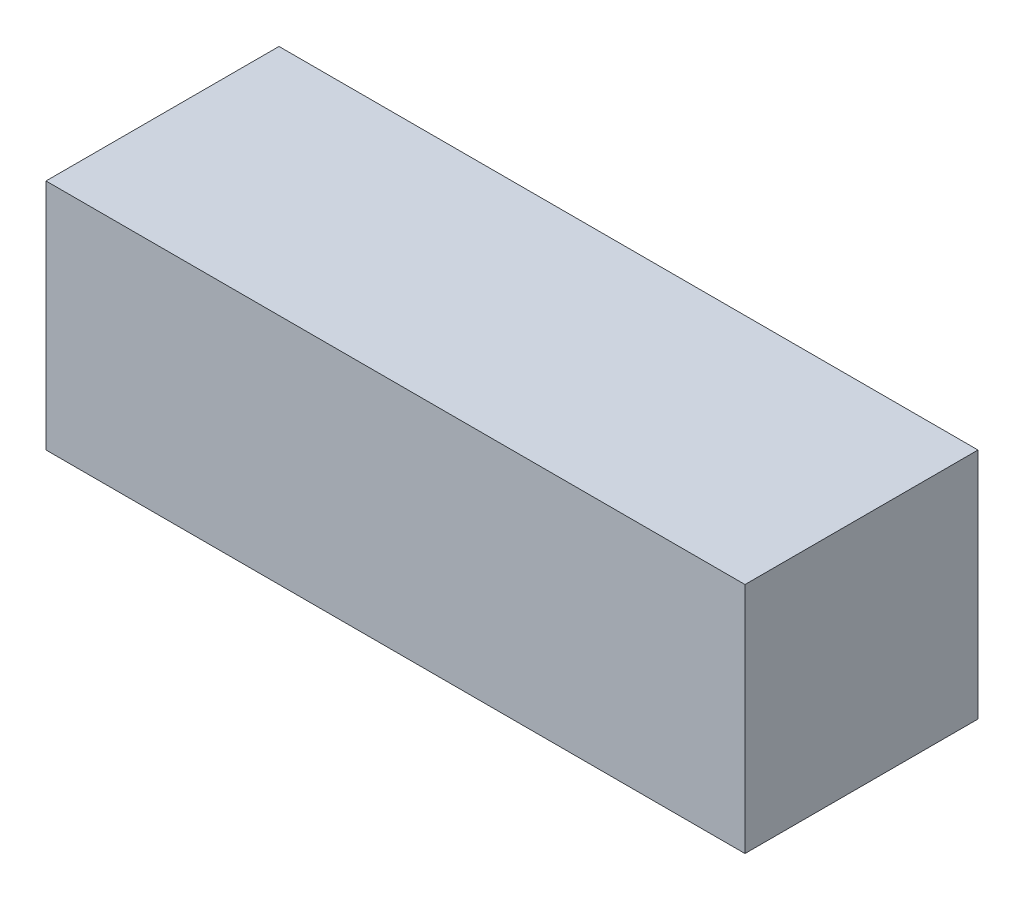
SolidWorks part; units mm, degrees
material "Alloy Steel"
ref_plane "Front Plane" through (0, 0, 0) normal (0, 0, 1) x (1, 0, 0)
ref_plane "Top Plane" through (0, 0, 0) normal (0, 1, 0) x (1, 0, 0)
ref_plane "Right Plane" through (0, 0, 0) normal (1, 0, 0) x (0, 0, -1)
sketch "Sketch1" plane through (0, 0, 0) normal (1, 0, 0) x (0, 0, -1)
  line L1 (-2, -2) -> (2, -2)
  line L2 (-2, -2) -> (-2, 2)
  line L3 (-2, 2) -> (2, 2)
  line L4 (2, -2) -> (2, 2)
  line L5 (-2, -2) -> (2, 2) construction
  line L6 (-2, 2) -> (2, -2) construction
  point P0 (0, 0)
  dimension "D1" = 4
  dimension "D2" = 4
extrude "Boss-Extrude1" add sketch "Sketch1" along normal mid plane 12
sketch "Sketch2" [suppressed] plane through (0, 2, 0) normal (0, 1, 0) x (1, 0, 0)
  line L0 (6, -2) -> (-6, -2) construction
  line L1 (6, 2) -> (2, 2)
  line L2 (6, 2) -> (6, -2)
  line L3 (6, -2) -> (2, -2)
  line L4 (2, 2) -> (2, -2)
  dimension "D1" = 4
extrude "Cut-Extrude1" [suppressed] cut sketch "Sketch2" against normal through all
equation "\"shaft-diameter\"= 20mm"
equation "\"key-length\"= 12mm"
equation "\"key-width\"= 4mm"
equation "\"D1@Boss-Extrude1\"=\"key-length\""
equation "\"D2@Sketch1\"=\"key-width\""
